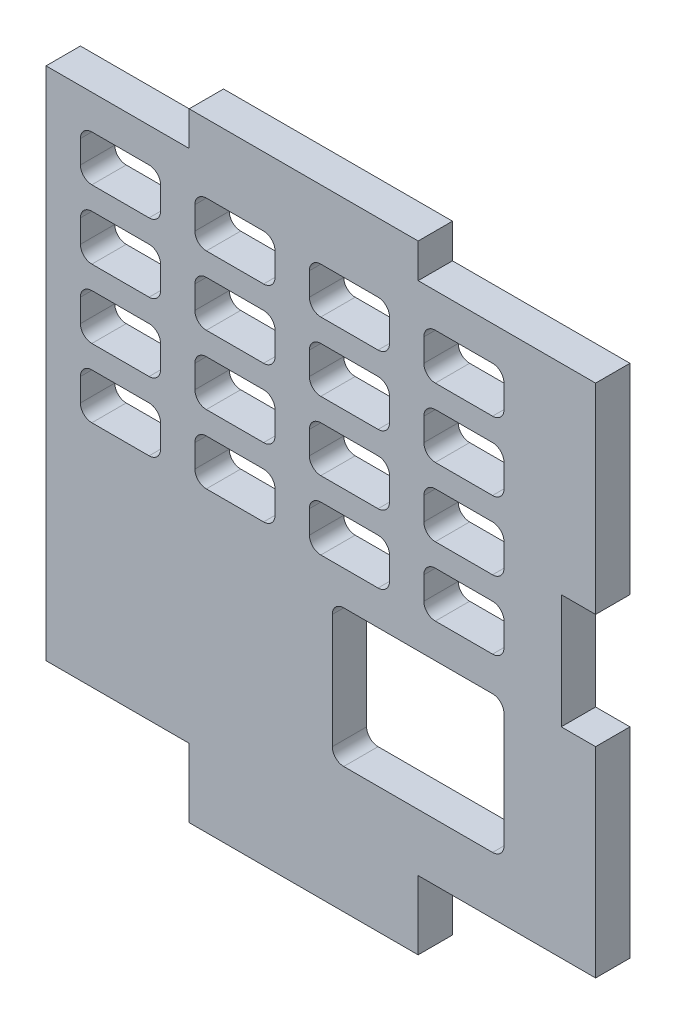
SolidWorks part; units mm, degrees
ref_plane "Front Plane" through (0, 0, 0) normal (0, 0, 1) x (1, 0, 0)
ref_plane "Top Plane" through (0, 0, 0) normal (0, 1, 0) x (1, 0, 0)
ref_plane "Right Plane" through (0, 0, 0) normal (1, 0, 0) x (0, 0, -1)
sketch "Sketch1" plane through (0, 0, 0) normal (0, 0, 1) x (1, 0, 0)
  line L0 (0, 0) -> (0, 45)
  line L1 (0, 45) -> (12.5, 45)
  line L2 (12.5, 45) -> (12.5, 48)
  line L3 (12.5, 48) -> (32.5, 48)
  line L4 (32.5, 48) -> (32.5, 45)
  line L5 (32.5, 45) -> (48, 45)
  line L6 (48, 45) -> (48, 27.5)
  line L7 (48, 27.5) -> (45, 27.5)
  line L8 (45, 27.5) -> (45, 17.5)
  line L9 (45, 17.5) -> (48, 17.5)
  line L10 (48, 17.5) -> (48, 0)
  line L11 (48, 0) -> (32.5, 0)
  line L12 (32.5, 0) -> (32.5, -6)
  line L13 (32.5, -6) -> (12.5, -6)
  line L14 (12.5, -6) -> (12.5, 0)
  line L15 (12.5, 0) -> (0, 0)
  dimension "D1" = 6
  dimension "D2" = 20
  dimension "D3" = 45
  dimension "D4" = 10
  dimension "D5" = 3
  dimension "D6" = 48
  dimension "D7" = 12.5
extrude "Boss-Extrude1" add sketch "Sketch1" along normal blind 3
sketch "Sketch2" plane through (0, 0, 3) normal (0, 0, 1) x (1, 0, 0)
  line L0 (45, 17.5) -> (45, 27.5) construction
  line L1 (25, 17) -> (40, 17)
  line L2 (25, 17) -> (25, 5)
  line L3 (25, 5) -> (40, 5)
  line L4 (40, 17) -> (40, 5)
  line L5 (32.5, 0) -> (48, 0) construction
  dimension "D1" = 5
  dimension "D2" = 5
  dimension "D3" = 15
  dimension "D4" = 12
extrude "Cut-Extrude1" cut sketch "Sketch2" against normal through all
fillet "Fillet1" radius 1 4 edges at (25, 5, 1.5) (40, 5, 1.5) (40, 17, 1.5) (25, 17, 1.5)
sketch "Sketch3" plane through (0, 0, 3) normal (0, 0, 1) x (1, 0, 0)
  line L0 (12.5, 45) -> (0, 45) construction
  line L1 (4, 42) -> (9, 42)
  line L2 (3, 41) -> (3, 39)
  line L3 (4, 38) -> (9, 38)
  line L4 (10, 41) -> (10, 39)
  line L5 (0, 45) -> (0, 0) construction
  arc A0 (9, 38) -> (10, 39) centre (9, 39) ccw
  arc A1 (9, 42) -> (10, 41) centre (9, 41) cw
  arc A2 (3, 39) -> (4, 38) centre (4, 39) ccw
  arc A3 (4, 42) -> (3, 41) centre (4, 41) ccw
  point P10 (10, 38)
  point P13 (10, 42)
  point P18 (3, 42)
  dimension "D5" = 1
  dimension "D1" = 3
  dimension "D2" = 3
  dimension "D3" = 7
  dimension "D4" = 4
extrude "Cut-Extrude2" cut sketch "Sketch3" against normal through all
pattern_linear "LPattern1" count 4 spacing 10 along (1, 0, 0) count 4 spacing 6 along (0, -1, 0) of "Cut-Extrude2"
